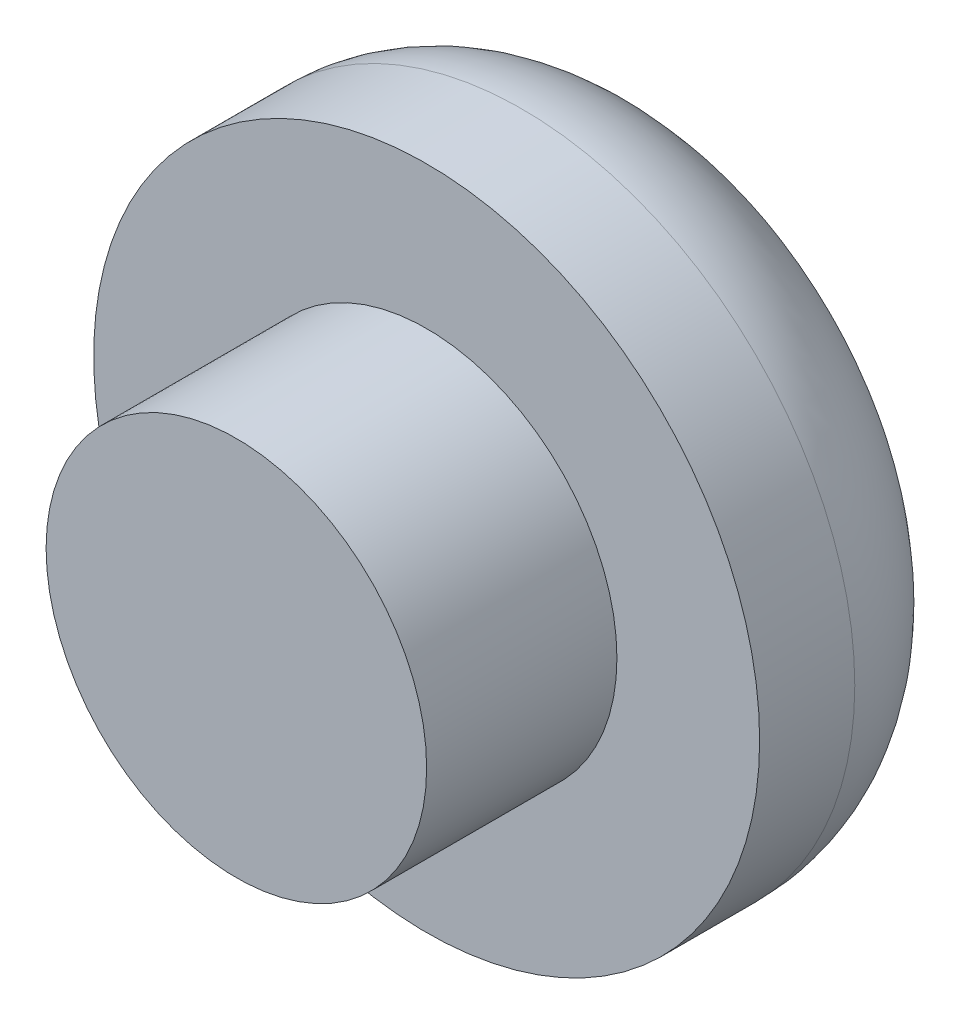
SolidWorks part; units mm, degrees
ref_plane "GAUCHE" through (0, 0, 0) normal (0, 0, 1) x (1, 0, 0)
ref_plane "Plan2" through (0, 0, 0) normal (0, 1, 0) x (1, 0, 0)
ref_plane "Plan3" through (0, 0, 0) normal (1, 0, 0) x (0, 0, -1)
sketch "Esquisse1" plane through (0, 0, 0) normal (0, 0, 1) x (1, 0, 0)
  circle A0 centre (0, 0) radius 7
  dimension "D1" = 14
extrude "Base-Extrusion" add sketch "Esquisse1" along normal blind 5
fillet "Congé1" radius 3
sketch "Esquisse2" plane through (0, 0, 5) normal (0, 0, 1) x (1, 0, 0)
  circle A0 centre (0, 0) radius 4
  dimension "D1" = 8
extrude "Boss.-Extru.2" add sketch "Esquisse2" along normal blind 4
